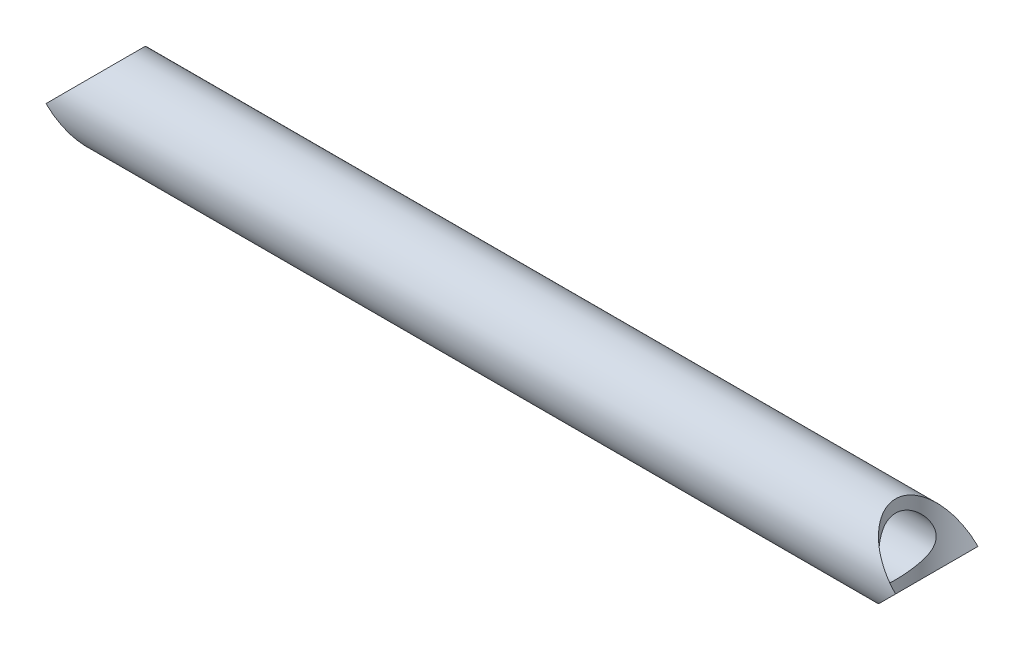
SolidWorks part; units mm, degrees
ref_plane "Front Plane" through (0, 0, 0) normal (0, 0, 1) x (1, 0, 0)
ref_plane "Top Plane" through (0, 0, 0) normal (0, 1, 0) x (1, 0, 0)
ref_plane "Right Plane" through (0, 0, 0) normal (1, 0, 0) x (0, 0, -1)
sketch "Sketch2" plane through (0, 0, 0) normal (0, 1, 0) x (1, 0, 0)
  line L0 (0, 0) -> (1030, 0)
  dimension "D1" = 1030
sketch "Sketch3" plane through (0, 0, 0) normal (1, 0, 0) x (0, 0, -1)
  circle A0 centre (0, 0) radius 50
  circle A1 centre (0, 0) radius 35
  dimension "D1" = 100
  dimension "D2" = 15
sweep "Sweep1" add profiles "Sketch3" path "Sketch2"
sketch "Sketch4" plane through (0, 0, 0) normal (0, 1, 0) x (1, 0, 0)
  line L0 (1030, -50) -> (1030, 50) construction
  circle A0 centre (0, 0) radius 50
  circle A1 centre (1030, 0) radius 50
  dimension "D1" = 100
  dimension "D2" = 100
extrude "Cut-Extrude1" cut sketch "Sketch4" against normal through all both and the other way through all
equation "\"hatchHoleDiameter\"= 600mm"
equation "\"hullThickness\"= 120mm"
equation "\"gasketHullInterconnectWidth\"= 100mm"
equation "\"collarThickness\"= 15"
equation "\"hatchTunnelLength\"=200"
equation "\"oRingDiameter\"=2"
equation "\"boltPatternRadiusInterconnect\"=500"
equation "\"interconnectBoltDiameter\"=30"
equation "\"hatchShaftDiameter\"=20"
equation "\"hatchMinima\"=50"
equation "\"hullDiameter\"=2000"
equation "\"hatchMaxima\"=180"
equation "\"bushingFlatHatch\"=15"
equation "\"hingePivotDiameter\"=20"
equation "\"handleWidth\"=250"
equation "\"handleHeight\"=160"
equation "\"handleThickness\"=25"
equation "\"FrameLength\"= 4300"
equation "\"FrameMidLength\"= 3000"
equation "\"TubeOD\"= 100"
equation "\"FrameBackFlat\"= 800"
equation "\"TubeWall\"=15"
equation "\"TopMemberAngle\"=120"
equation "\"FrameHight\"= 2500"
equation "\"D2@Sketch3\"=\"TubeWall\""
